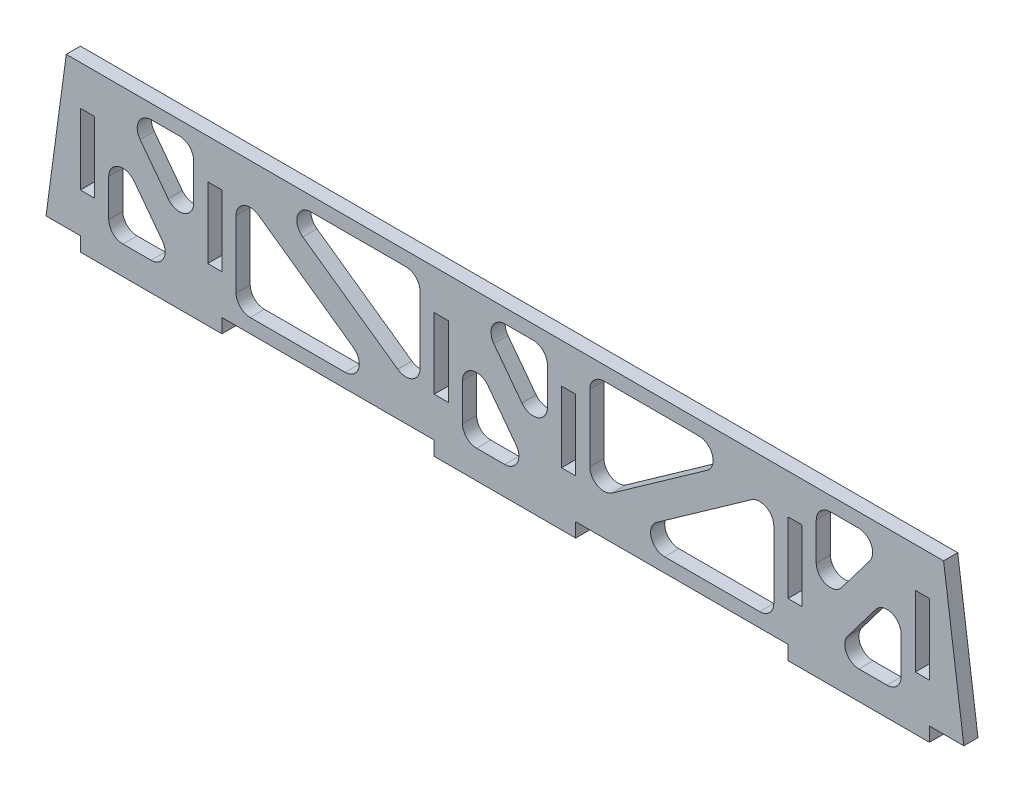
SolidWorks part; units mm, degrees
material "AISI 4340 Steel, normalized"
ref_plane "Front Plane" through (0, 0, 0) normal (0, 0, 1) x (1, 0, 0)
ref_plane "Top Plane" through (0, 0, 0) normal (0, 1, 0) x (1, 0, 0)
ref_plane "Right Plane" through (0, 0, 0) normal (1, 0, 0) x (0, 0, -1)
sketch "Sketch1" plane through (0, 0, 0) normal (0, 0, 1) x (1, 0, 0)
  line B0 (0, 0) -> (0, -42.4264) construction
  line B1 (124, 0) -> (-124, 0)
  line B2 (-124, 0) -> (-129.726, -42.4264)
  line B3 (-129.726, -42.4264) -> (129.726, -42.4264)
  line B4 (129.726, -42.4264) -> (124, 0)
  line B5 (-112, -23.8919) -> (-112, -34.4264)
  line B6 (-96.8609, -32.0177) -> (-104.8065, -21.4833)
  line B7 (-108, -38.4264) -> (-100.0544, -38.4264)
  line B8 (-88, -18.5345) -> (-88, -8)
  line B9 (-92, -4) -> (-99.9456, -4)
  line B10 (-103.1391, -10.4087) -> (-95.1935, -20.9431)
  line B11 (-72, -38.4264) -> (-45.1701, -38.4264)
  line B12 (-76, -15.4548) -> (-76, -34.4264)
  line B13 (-42.8607, -31.1604) -> (-69.6906, -12.1888)
  line B14 (-57.1393, -11.266) -> (-30.3094, -30.2376)
  line B15 (-24, -26.9716) -> (-24, -8)
  line B16 (-28, -4) -> (-54.8299, -4)
  line B17 (12, -18.5345) -> (12, -8)
  line B18 (8, -4) -> (0.0544, -4)
  line B19 (-3.1391, -10.4087) -> (4.8065, -20.9431)
  line B20 (3.1391, -32.0177) -> (-4.8065, -21.4833)
  line B21 (-8, -38.4264) -> (-0.0544, -38.4264)
  line B22 (-12, -23.8919) -> (-12, -34.4264)
  arc B23 (-112, -34.4264) -> (-108, -38.4264) centre (-108, -34.4264) ccw
  arc B24 (-104.8065, -21.4833) -> (-112, -23.8919) centre (-108, -23.8919) ccw
  arc B25 (-100.0544, -38.4264) -> (-96.8609, -32.0177) centre (-100.0544, -34.4264) ccw
  arc B26 (-88, -8) -> (-92, -4) centre (-92, -8) ccw
  arc B27 (-95.1935, -20.9431) -> (-88, -18.5345) centre (-92, -18.5345) ccw
  arc B28 (-99.9456, -4) -> (-103.1391, -10.4087) centre (-99.9456, -8) ccw
  arc B29 (-76, -34.4264) -> (-72, -38.4264) centre (-72, -34.4264) ccw
  arc B30 (-45.1701, -38.4264) -> (-42.8607, -31.1604) centre (-45.1701, -34.4264) ccw
  arc B31 (-69.6906, -12.1888) -> (-76, -15.4548) centre (-72, -15.4548) ccw
  arc B32 (-30.3094, -30.2376) -> (-24, -26.9716) centre (-28, -26.9716) ccw
  arc B33 (-24, -8) -> (-28, -4) centre (-28, -8) ccw
  arc B34 (-54.8299, -4) -> (-57.1393, -11.266) centre (-54.8299, -8) ccw
  arc B35 (4.8065, -20.9431) -> (12, -18.5345) centre (8, -18.5345) ccw
  arc B36 (12, -8) -> (8, -4) centre (8, -8) ccw
  arc B37 (0.0544, -4) -> (-3.1391, -10.4087) centre (0.0544, -8) ccw
  arc B38 (-0.0544, -38.4264) -> (3.1391, -32.0177) centre (-0.0544, -34.4264) ccw
  arc B39 (-12, -34.4264) -> (-8, -38.4264) centre (-8, -34.4264) ccw
  arc B40 (-4.8065, -21.4833) -> (-12, -23.8919) centre (-8, -23.8919) ccw
sketch_block_instance "Block-pedalbox top-1"
sketch_block "Block-pedalbox top"
sketch "Sketch2" plane through (0, 0, 0) normal (0, 0, 1) x (1, 0, 0)
  line L0 (124, 0) -> (-124, 0) construction
  line L1 (-124, 0) -> (-129.726, -42.4264) construction
  line L2 (-129.726, -42.4264) -> (129.726, -42.4264) construction
  line L3 (129.726, -42.4264) -> (124, 0) construction
  line L4 (-88, -18.5345) -> (-88, -8) construction
  line L5 (-92, -4) -> (-99.9456, -4) construction
  line L6 (-103.1391, -10.4087) -> (-95.1935, -20.9431) construction
  line L7 (-108, -38.4264) -> (-100.0544, -38.4264) construction
  line L8 (-112, -23.8919) -> (-112, -34.4264) construction
  line L9 (-96.8609, -32.0177) -> (-104.8065, -21.4833) construction
  line L10 (-57.1393, -11.266) -> (-30.3094, -30.2376) construction
  line L11 (-24, -26.9716) -> (-24, -8) construction
  line L12 (-28, -4) -> (-54.8299, -4) construction
  line L13 (-42.8607, -31.1604) -> (-69.6906, -12.1888) construction
  line L14 (-76, -15.4548) -> (-76, -34.4264) construction
  line L15 (-72, -38.4264) -> (-45.1701, -38.4264) construction
  line L16 (3.1391, -32.0177) -> (-4.8065, -21.4833) construction
  line L17 (-12, -23.8919) -> (-12, -34.4264) construction
  line L18 (-8, -38.4264) -> (-0.0544, -38.4264) construction
  line L19 (12, -18.5345) -> (12, -8) construction
  line L20 (-3.1391, -10.4087) -> (4.8065, -20.9431) construction
  line L21 (8, -4) -> (0.0544, -4) construction
  line L22 (124, 0) -> (-124, 0)
  line L23 (-124, 0) -> (-129.726, -42.4264)
  line L24 (-129.726, -42.4264) -> (-120, -42.4264)
  line L25 (129.726, -42.4264) -> (124, 0)
  line L26 (-88, -18.5345) -> (-88, -8)
  line L27 (-92, -4) -> (-99.9456, -4)
  line L28 (-103.1391, -10.4087) -> (-95.1935, -20.9431)
  line L29 (-108, -38.4264) -> (-100.0544, -38.4264)
  line L30 (-112, -23.8919) -> (-112, -34.4264)
  line L31 (-96.8609, -32.0177) -> (-104.8065, -21.4833)
  line L32 (-57.1393, -11.266) -> (-30.3094, -30.2376)
  line L33 (-24, -26.9716) -> (-24, -8)
  line L34 (-28, -4) -> (-54.8299, -4)
  line L35 (-42.8607, -31.1604) -> (-69.6906, -12.1888)
  line L36 (-76, -15.4548) -> (-76, -34.4264)
  line L37 (-72, -38.4264) -> (-45.1701, -38.4264)
  line L38 (3.1391, -32.0177) -> (-4.8065, -21.4833)
  line L39 (-12, -23.8919) -> (-12, -34.4264)
  line L40 (-8, -38.4264) -> (-0.0544, -38.4264)
  line L41 (12, -18.5345) -> (12, -8)
  line L42 (-3.1391, -10.4087) -> (4.8065, -20.9431)
  line L43 (8, -4) -> (0.0544, -4)
  line L44 (0, -42.4264) -> (0, 0) construction
  line L45 (0, 0) -> (0, 18.1301) construction
  line L46 (112, -23.8919) -> (112, -34.4264)
  line L47 (96.8609, -32.0177) -> (104.8065, -21.4833)
  line L48 (108, -38.4264) -> (100.0544, -38.4264)
  line L49 (103.1391, -10.4087) -> (95.1935, -20.9431)
  line L50 (92, -4) -> (99.9456, -4)
  line L51 (88, -18.5345) -> (88, -8)
  line L52 (28, -4) -> (54.8299, -4)
  line L53 (24, -26.9716) -> (24, -8)
  line L54 (57.1393, -11.266) -> (30.3094, -30.2376)
  line L55 (72, -38.4264) -> (45.1701, -38.4264)
  line L56 (76, -15.4548) -> (76, -34.4264)
  line L57 (42.8607, -31.1604) -> (69.6906, -12.1888)
  line L58 (-126.863, -21.2132) -> (0, -21.2132) construction
  line L59 (-116, -31.2132) -> (-116, -11.2132)
  line L60 (-20, -31.2132) -> (-16, -31.2132)
  line L61 (-20, -31.2132) -> (-20, -11.2132)
  line L62 (-20, -11.2132) -> (-16, -11.2132)
  line L63 (-16, -31.2132) -> (-16, -11.2132)
  line L64 (-18, -11.2132) -> (-18, -31.2132) construction
  line L65 (-20, -21.2132) -> (-16, -21.2132) construction
  line L66 (-120, -11.2132) -> (-116, -11.2132)
  line L67 (-120, -31.2132) -> (-120, -11.2132)
  line L68 (-120, -31.2132) -> (-116, -31.2132)
  line L69 (-84, -31.2132) -> (-84, -11.2132)
  line L70 (-84, -11.2132) -> (-80, -11.2132)
  line L71 (-80, -31.2132) -> (-80, -11.2132)
  line L72 (-84, -31.2132) -> (-80, -31.2132)
  line L73 (20, -11.2132) -> (16, -11.2132)
  line L74 (16, -31.2132) -> (16, -11.2132)
  line L75 (20, -31.2132) -> (16, -31.2132)
  line L76 (20, -31.2132) -> (20, -11.2132)
  line L77 (84, -31.2132) -> (80, -31.2132)
  line L78 (80, -31.2132) -> (80, -11.2132)
  line L79 (84, -11.2132) -> (80, -11.2132)
  line L80 (84, -31.2132) -> (84, -11.2132)
  line L81 (120, -31.2132) -> (116, -31.2132)
  line L82 (120, -31.2132) -> (120, -11.2132)
  line L83 (120, -11.2132) -> (116, -11.2132)
  line L84 (116, -31.2132) -> (116, -11.2132)
  line L85 (-20, -46.4264) -> (20, -46.4264)
  line L86 (-20, -46.4264) -> (-20, -42.4264)
  line L87 (20, -46.4264) -> (20, -42.4264)
  line L88 (20, -42.4264) -> (80, -42.4264)
  line L89 (120, -21.2132) -> (126.863, -21.2132) construction
  line L90 (80, -46.4264) -> (80, -42.4264)
  line L91 (80, -46.4264) -> (120, -46.4264)
  line L92 (120, -46.4264) -> (120, -42.4264)
  line L93 (120, -42.4264) -> (129.726, -42.4264)
  line L94 (-80, -46.4264) -> (-80, -42.4264)
  line L95 (-120, -46.4264) -> (-80, -46.4264)
  line L96 (-120, -46.4264) -> (-120, -42.4264)
  line L97 (-80, -42.4264) -> (-20, -42.4264)
  arc A0 (-88, -8) -> (-92, -4) centre (-92, -8) ccw construction
  arc A1 (-99.9456, -4) -> (-103.1391, -10.4087) centre (-99.9456, -8) ccw construction
  arc A2 (-95.1935, -20.9431) -> (-88, -18.5345) centre (-92, -18.5345) ccw construction
  arc A3 (-112, -34.4264) -> (-108, -38.4264) centre (-108, -34.4264) ccw construction
  arc A4 (-104.8065, -21.4833) -> (-112, -23.8919) centre (-108, -23.8919) ccw construction
  arc A5 (-100.0544, -38.4264) -> (-96.8609, -32.0177) centre (-100.0544, -34.4264) ccw construction
  arc A6 (-30.3094, -30.2376) -> (-24, -26.9716) centre (-28, -26.9716) ccw construction
  arc A7 (-24, -8) -> (-28, -4) centre (-28, -8) ccw construction
  arc A8 (-54.8299, -4) -> (-57.1393, -11.266) centre (-54.8299, -8) ccw construction
  arc A9 (-69.6906, -12.1888) -> (-76, -15.4548) centre (-72, -15.4548) ccw construction
  arc A10 (-76, -34.4264) -> (-72, -38.4264) centre (-72, -34.4264) ccw construction
  arc A11 (-45.1701, -38.4264) -> (-42.8607, -31.1604) centre (-45.1701, -34.4264) ccw construction
  arc A12 (-4.8065, -21.4833) -> (-12, -23.8919) centre (-8, -23.8919) ccw construction
  arc A13 (-12, -34.4264) -> (-8, -38.4264) centre (-8, -34.4264) ccw construction
  arc A14 (-0.0544, -38.4264) -> (3.1391, -32.0177) centre (-0.0544, -34.4264) ccw construction
  arc A15 (4.8065, -20.9431) -> (12, -18.5345) centre (8, -18.5345) ccw construction
  arc A16 (0.0544, -4) -> (-3.1391, -10.4087) centre (0.0544, -8) ccw construction
  arc A17 (12, -8) -> (8, -4) centre (8, -8) ccw construction
  arc A18 (-88, -8) -> (-92, -4) centre (-92, -8) ccw
  arc A19 (-99.9456, -4) -> (-103.1391, -10.4087) centre (-99.9456, -8) ccw
  arc A20 (-95.1935, -20.9431) -> (-88, -18.5345) centre (-92, -18.5345) ccw
  arc A21 (-112, -34.4264) -> (-108, -38.4264) centre (-108, -34.4264) ccw
  arc A22 (-104.8065, -21.4833) -> (-112, -23.8919) centre (-108, -23.8919) ccw
  arc A23 (-100.0544, -38.4264) -> (-96.8609, -32.0177) centre (-100.0544, -34.4264) ccw
  arc A24 (-30.3094, -30.2376) -> (-24, -26.9716) centre (-28, -26.9716) ccw
  arc A25 (-24, -8) -> (-28, -4) centre (-28, -8) ccw
  arc A26 (-54.8299, -4) -> (-57.1393, -11.266) centre (-54.8299, -8) ccw
  arc A27 (-69.6906, -12.1888) -> (-76, -15.4548) centre (-72, -15.4548) ccw
  arc A28 (-76, -34.4264) -> (-72, -38.4264) centre (-72, -34.4264) ccw
  arc A29 (-45.1701, -38.4264) -> (-42.8607, -31.1604) centre (-45.1701, -34.4264) ccw
  arc A30 (-4.8065, -21.4833) -> (-12, -23.8919) centre (-8, -23.8919) ccw
  arc A31 (-12, -34.4264) -> (-8, -38.4264) centre (-8, -34.4264) ccw
  arc A32 (-0.0544, -38.4264) -> (3.1391, -32.0177) centre (-0.0544, -34.4264) ccw
  arc A33 (4.8065, -20.9431) -> (12, -18.5345) centre (8, -18.5345) ccw
  arc A34 (0.0544, -4) -> (-3.1391, -10.4087) centre (0.0544, -8) ccw
  arc A35 (12, -8) -> (8, -4) centre (8, -8) ccw
  arc A36 (112, -34.4264) -> (108, -38.4264) centre (108, -34.4264) cw
  arc A37 (104.8065, -21.4833) -> (112, -23.8919) centre (108, -23.8919) cw
  arc A38 (100.0544, -38.4264) -> (96.8609, -32.0177) centre (100.0544, -34.4264) cw
  arc A39 (95.1935, -20.9431) -> (88, -18.5345) centre (92, -18.5345) cw
  arc A40 (99.9456, -4) -> (103.1391, -10.4087) centre (99.9456, -8) cw
  arc A41 (88, -8) -> (92, -4) centre (92, -8) cw
  arc A42 (54.8299, -4) -> (57.1393, -11.266) centre (54.8299, -8) cw
  arc A43 (24, -8) -> (28, -4) centre (28, -8) cw
  arc A44 (30.3094, -30.2376) -> (24, -26.9716) centre (28, -26.9716) cw
  arc A45 (45.1701, -38.4264) -> (42.8607, -31.1604) centre (45.1701, -34.4264) cw
  arc A46 (76, -34.4264) -> (72, -38.4264) centre (72, -34.4264) cw
  arc A47 (69.6906, -12.1888) -> (76, -15.4548) centre (72, -15.4548) cw
  point P101 (-18, -21.2132)
  point P130 (0, -46.4264)
  dimension "D1" = 20
  dimension "D2" = 4
  dimension "D3" = 16
  dimension "D6" = 32
  dimension "D7" = 60
  dimension "D8" = 20
  dimension "D9" = 4
  dimension "D10" = 2
  dimension "D4" = 2
  dimension "D5" = 2
  dimension "D11" = 2
extrude "Boss-Extrude1" add sketch "Sketch2" along normal blind 4
